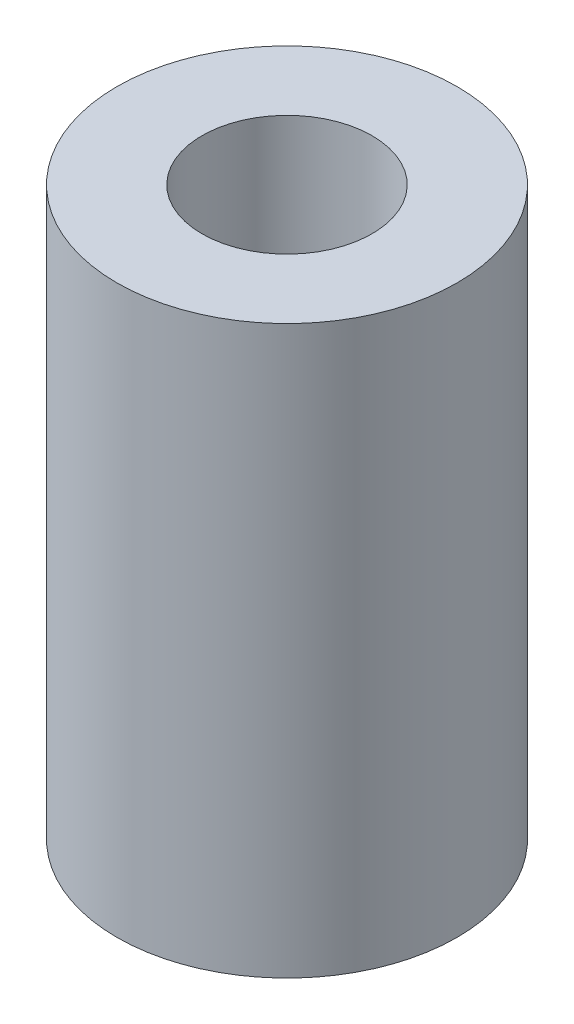
SolidWorks part; units mm, degrees
ref_plane "Front Plane" through (0, 0, 0) normal (0, 0, 1) x (1, 0, 0)
ref_plane "Top Plane" through (0, 0, 0) normal (0, 1, 0) x (1, 0, 0)
ref_plane "Right Plane" through (0, 0, 0) normal (1, 0, 0) x (0, 0, -1)
sketch "Sketch1" plane through (0, 0, 0) normal (0, 1, 0) x (1, 0, 0)
  circle A0 centre (0, 0) radius 1.5
  circle A1 centre (0, 0) radius 3
  dimension "D1" = 3
  dimension "D2" = 6
extrude "Boss-Extrude1" add sketch "Sketch1" along normal blind 10
